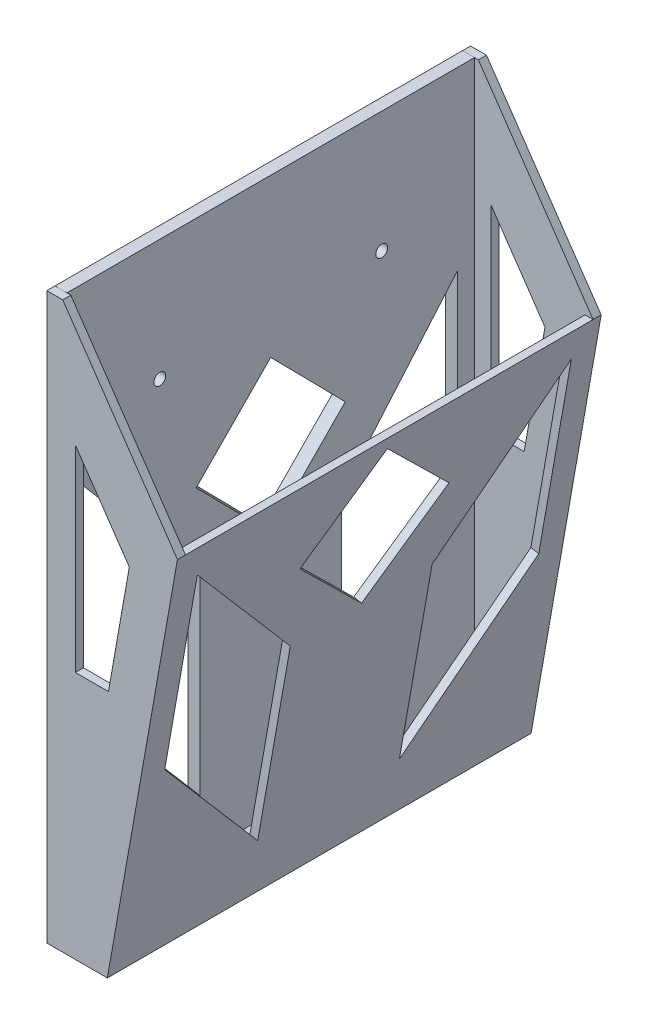
SolidWorks part; units mm, degrees
ref_plane "Front Plane" through (0, 0, 0) normal (0, 0, 1) x (1, 0, 0)
ref_plane "Top Plane" through (0, 0, 0) normal (0, 1, 0) x (1, 0, 0)
ref_plane "Right Plane" through (0, 0, 0) normal (1, 0, 0) x (0, 0, -1)
sketch "Esquisse2" plane through (0, 0, 0) normal (0, 0, 1) x (1, 0, 0)
  line L0 (0, 0) -> (0, 140)
  line L1 (0, 140) -> (3.9428, 140)
  line L2 (32.3648, 98.4808) -> (15, 0)
  line L3 (15, 0) -> (0, 0)
  line L4 (3.9428, 140) -> (32.3648, 98.4808)
  dimension "D1" = 140
  dimension "D2" = 15
  dimension "D3" = 100
  dimension "D4" = 100
extrude "Boss.-Extru.1" add sketch "Esquisse2" along normal blind 2
sketch "Esquisse4" plane through (0, 0, 2) normal (0, 0, 1) x (1, 0, 0)
  line L0 (0, 0) -> (0, 3.0061)
  line L1 (0, 140) -> (0, 0) construction
  line L2 (0, 3.0061) -> (15.5301, 3.0061)
  line L3 (15, 0) -> (32.3648, 98.4808) construction
  line L4 (15.5301, 3.0061) -> (15, 0)
  line L5 (15, 0) -> (0, 0)
extrude "Boss.-Extru.2" add sketch "Esquisse4" along normal blind 102
pattern_linear "Répétition linéaire1" count 2 spacing 103 along (0, 0, 1) of "Boss.-Extru.1"
sketch "Esquisse5" plane through (0, 3.0061, 0) normal (0, 1, 0) x (1, 0, 0)
  line L0 (15.5301, -103) -> (0, -103) construction
  line L1 (0, -2) -> (2.9757, -2)
  line L2 (0, -2) -> (0, -103)
  line L3 (0, -103) -> (2.9757, -103)
  line L4 (2.9757, -2) -> (2.9757, -103)
extrude "Boss.-Extru.3" add sketch "Esquisse5" along normal blind 137
sketch "Esquisse6" plane through (0, 3.0061, 0) normal (0, 1, 0) x (1, 0, 0)
  line L0 (15.5301, -103) -> (2.9757, -103) construction
  line L1 (15.5301, -2) -> (13.5301, -2)
  line L2 (15.5301, -2) -> (15.5301, -103)
  line L3 (15.5301, -103) -> (13.5301, -103)
  line L4 (13.5301, -2) -> (13.5301, -103)
  point P7 (12.1787, -103)
sweep "Balayage1" add profiles "Esquisse6" path edge at (23.9474, 50.7434, 103)
sketch "Esquisse8" plane through (14.5477, -2.5652, 0) normal (0.9848, -0.1736, 0) x (0, 0, -1)
  line L0 (-52.5, 102.6047) -> (-52.5, 2.6047) construction
  line L1 (-103, 102.6047) -> (-2, 102.6047) construction
  line L2 (-105, 2.6047) -> (0, 2.6047) construction
ref_plane "Plan3" through (0, 0, 52.5) normal (0, 0, 1) x (-0.1736, -0.9848, 0)
sketch "Esquisse9" plane through (2.9757, 0, 0) normal (1, 0, 0) x (0, 0, -1)
  circle A0 centre (-80, 110) radius 1.4621
extrude "Enlèv. mat.-Extru.8" cut sketch "Esquisse9" against normal blind 10
mirror "Symétrie3" about plane through (0, 0, 52.5) normal (0, 0, 1) of "Enlèv. mat.-Extru.8"
sketch "Esquisse11" plane through (14.5477, -2.5652, 0) normal (0.9848, -0.1736, 0) x (0, 0, -1)
  line L0 (-6.1604, 48.9683) -> (-6.1604, 95.4896)
  line L1 (-6.1604, 48.9683) -> (-34.9395, 15.957)
  line L2 (-6.1604, 95.4896) -> (-34.9395, 62.4783)
  line L3 (-34.9395, 15.957) -> (-34.9395, 62.4783)
extrude "Enlèv. mat.-Extru.10" cut sketch "Esquisse11" against normal through all
mirror "Symétrie4" about plane through (0, 0, 52.5) normal (0, 0, 1) of "Enlèv. mat.-Extru.10"
sketch "Esquisse13" plane through (14.5477, -2.5652, 0) normal (0.9848, -0.1736, 0) x (0, 0, -1)
  line L0 (-70.9687, 81.4236) -> (-52.5, 62.955)
  line L1 (-70.9687, 81.4236) -> (-52.5, 99.8923)
  line L2 (-52.5, 62.955) -> (-34.0313, 81.4236)
  line L3 (-52.5, 99.8923) -> (-34.0313, 81.4236)
  line L4 (-70.9687, 81.4236) -> (-34.0313, 81.4236) construction
  line L5 (-52.5, 62.955) -> (-52.5, 99.8923) construction
  line L6 (-52.5, 82.4466) -> (-52.5, -82.4466) construction
  point P0 (-71.4687, 81.4236)
  point P1 (-52.5, 81.4236)
extrude "Enlèv. mat.-Extru.11" cut sketch "Esquisse13" against normal through all
sketch "Esquisse14" plane through (0, 0, 0) normal (0, 0, -1) x (-1, 0, 0)
  line L0 (-7.0761, 110.4185) -> (-7.0761, 61.6006)
  line L1 (-7.0761, 61.6006) -> (-15.2719, 61.6006)
  line L2 (-15.2719, 61.6006) -> (-20.438, 90.8992)
  line L3 (-20.438, 90.8992) -> (-7.0761, 110.4185)
  line L4 (-15, 0) -> (-32.3648, 98.4808) construction
  line L5 (-32.3648, 98.4808) -> (-3.9428, 140) construction
extrude "Enlèv. mat.-Extru.12" cut sketch "Esquisse14" against normal through all
